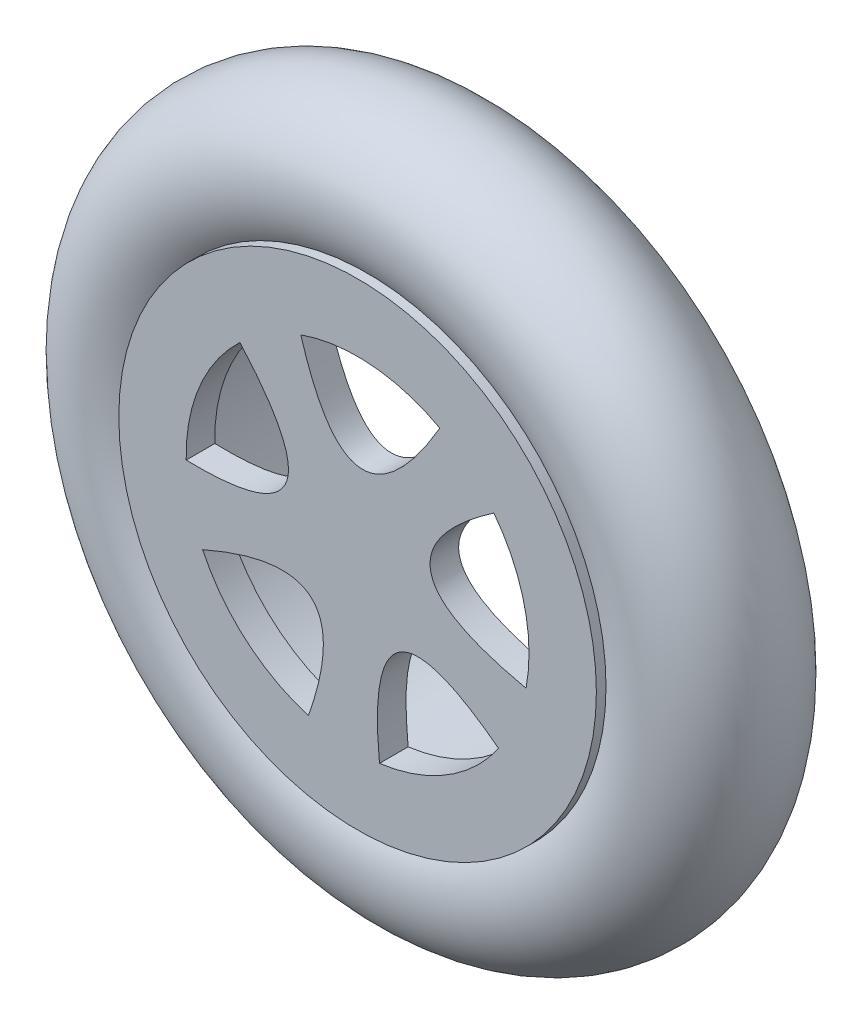
SolidWorks part; units mm, degrees
ref_plane "Front Plane" through (0, 0, 0) normal (0, 0, 1) x (1, 0, 0)
ref_plane "Top Plane" through (0, 0, 0) normal (0, 1, 0) x (1, 0, 0)
ref_plane "Right Plane" through (0, 0, 0) normal (1, 0, 0) x (0, 0, -1)
sketch "Sketch1" plane through (0, 0, 0) normal (0, 0, 1) x (1, 0, 0)
  circle A0 centre (0, 0) radius 123.825
  dimension "D1" = 247.65
extrude "Extrude1" add sketch "Sketch1" along normal blind 76.2
sketch "Sketch2" plane through (0, 0, 0) normal (0, 0, -1) x (-1, 0, 0)
  line L1 (0, 39.6863) -> (-37.744, 12.2638)
  line L2 (-37.744, 12.2638) -> (-23.327, -32.1069)
  line L3 (-23.327, -32.1069) -> (23.327, -32.1069)
  line L4 (23.327, -32.1069) -> (37.744, 12.2638)
  line L5 (37.744, 12.2638) -> (0, 39.6863)
  line L6 (-7.2268, 88.6058) -> (-42.6412, 78.006)
  line L7 (-42.6412, 78.006) -> (-70.6826, 53.9183)
  line L8 (-70.6826, 53.9183) -> (-86.5023, 20.5076)
  line L9 (-86.5023, 20.5076) -> (-87.365, -16.449)
  line L10 (-87.365, -16.449) -> (-73.1215, -50.5615)
  line L11 (-73.1215, -50.5615) -> (-46.2346, -75.9314)
  line L12 (-46.2346, -75.9314) -> (-11.3533, -88.1721)
  line L13 (-11.3533, -88.1721) -> (25.491, -85.167)
  line L14 (25.491, -85.167) -> (57.9278, -67.4358)
  line L15 (57.9278, -67.4358) -> (80.3482, -38.0443)
  line L16 (0, 58.4219) -> (-55.5625, 18.0534)
  line L17 (-55.5625, 18.0534) -> (-34.3395, -47.2643)
  line L18 (-34.3395, -47.2643) -> (34.3395, -47.2643)
  line L19 (34.3395, -47.2643) -> (55.5625, 18.0534)
  line L20 (55.5625, 18.0534) -> (0, 58.4219)
  line L21 (80.3482, -38.0443) -> (88.8758, -2.0746)
  line L22 (88.8758, -2.0746) -> (82.0359, 34.2538)
  line L23 (82.0359, 34.2538) -> (61.0113, 64.6594)
  line L24 (61.0113, 64.6594) -> (29.4372, 83.8848)
  line L25 (29.4372, 83.8848) -> (-7.2268, 88.6058)
  circle A0 centre (0, 0) radius 88.9
  circle A1 centre (0, 0) radius 32.1069 construction
  circle A2 centre (0, 0) radius 86.9573 construction
  circle A3 centre (0, 0) radius 47.2643 construction
  spline S0 degree 2 poles (-42.6412, 78.006) (3.8595, -1.919) (29.4372, 83.8848) knots 0 0 0 1 1 1
  spline S1 degree 2 poles (61.0113, 64.6594) (-0.6324, -4.2636) (88.8758, -2.0746) knots 0 0 0 1 1 1
  spline S2 degree 2 poles (80.3482, -38.0443) (-4.2504, -0.7161) (25.491, -85.167) knots 0 0 0 1 1 1
  spline S3 degree 2 poles (-11.3533, -88.1721) (-1.9945, 3.821) (-73.1215, -50.5615) knots 0 0 0 1 1 1
  spline S4 degree 2 poles (-87.365, -16.449) (3.0177, 3.0776) (-70.6826, 53.9183) knots 0 0 0 1 1 1
sketch "Sketch4" plane through (0, 0, 0) normal (0, 1, 0) x (1, 0, 0)
  line L0 (123.825, -76.2) -> (123.825, 0) construction
  line L1 (123.825, -5) -> (106.3698, -5)
  line L2 (123.825, -5) -> (123.825, -71.2)
  line L3 (123.825, -71.2) -> (106.3698, -71.2)
  line L4 (106.3698, -5) -> (106.3698, -71.2)
  line L5 (123.825, 0) -> (-123.825, 0) construction
  line L6 (-123.825, -76.2) -> (123.825, -76.2) construction
  line L7 (0, 0) -> (0, -100.868) construction
  dimension "D1" = 5
  dimension "D2" = 5
  dimension "D3" = 17.4552
revolve "Cut-Revolve1" cut sketch "Sketch4" angle 360 about L7
extrude "Extrude7" cut sketch "Sketch2" against normal through all contours L9 S4 L17 L16 L8 | L8 A0 | L9 A0 | L17 S4 L16 | L12 S3 L18 L17 L11 | L18 S3 L17 | L11 A0 | L12 A0 | L15 A0 | L15 S2 L19 L18 L14 | L19 S2 L18 | L14 A0 | L23 S1 L20 L19 L22 | L20 S1 L19 | L23 A0 | L22 A0 | L6 S0 L16 L20 L25 | L6 A0 | L16 S0 L20 | L25 A0
sketch "Sketch5" plane through (0, 0, 0) normal (0, 1, 0) x (1, 0, 0)
  line L0 (-123.825, -71.2) -> (-106.3698, -71.2)
  line L1 (123.825, -71.2) -> (-123.825, -71.2) construction
  line L2 (106.3698, -71.2) -> (-106.3698, -71.2) construction
  line L3 (-106.3698, -71.2) -> (-106.3698, -5)
  line L4 (-106.3698, -5) -> (106.3698, -5) construction
  line L5 (-106.3698, -5) -> (-123.825, -5)
  arc A0 (-123.825, -5) -> (-123.825, -71.2) centre (-144.4698, -38.1) ccw
  dimension "D1" = 38.1
  dimension "D2" = 17.4552
sketch "Sketch6" plane through (0, 0, 0) normal (1, 0, 0) x (0, 0, -1)
  line L0 (0, 0) -> (-61.3571, 0)
revolve "Revolve1" add sketch "Sketch5" angle 360 about L0
sketch "Sketch8" plane through (0, 0, 0) normal (0, 0, -1) x (-1, 0, 0)
  circle A0 centre (0, 0) radius 103.8766
extrude "Extrude8" cut sketch "Sketch8" against normal up to vertex (61.3571 mm away) up to point (0, 0, 61.3571)
